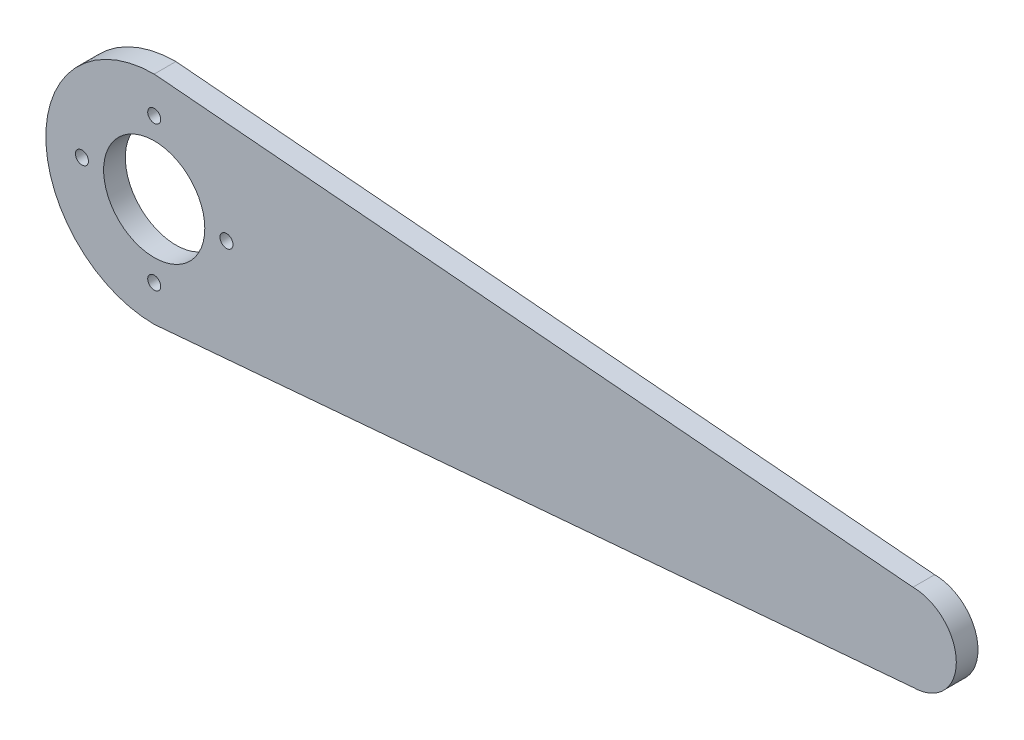
SolidWorks part; units mm, degrees
ref_plane "Front Plane" through (0, 0, 0) normal (0, 0, 1) x (1, 0, 0)
ref_plane "Top Plane" through (0, 0, 0) normal (0, 1, 0) x (1, 0, 0)
ref_plane "Right Plane" through (0, 0, 0) normal (1, 0, 0) x (0, 0, -1)
sketch "Sketch1" plane through (0, 0, 0) normal (0, 0, 1) x (1, 0, 0)
  line L0 (0, 0) -> (105, 0) construction
  line L1 (0, 15) -> (105, 6)
  line L2 (0, -15) -> (105, -6)
  line L3 (0, 0) -> (0, -10) construction
  circle A1 centre (0, 0) radius 15
  circle A2 centre (105, 0) radius 6
  circle A3 centre (0, -10) radius 0.9
  circle A4 centre (-10, 0) radius 0.9
  circle A5 centre (0, 10) radius 0.9
  circle A6 centre (10, 0) radius 0.9
  circle A7 centre (0, 0) radius 7
  point P20 (0, 0)
  dimension "D1" = 105
  dimension "D2" = 10
  dimension "D3" = 4
extrude "Boss-Extrude1" add sketch "Sketch1" along normal blind 3 contours A2 L1 A1 L2 | A2 | L1 A1 L2 A7 A6 A5 A4 A3
